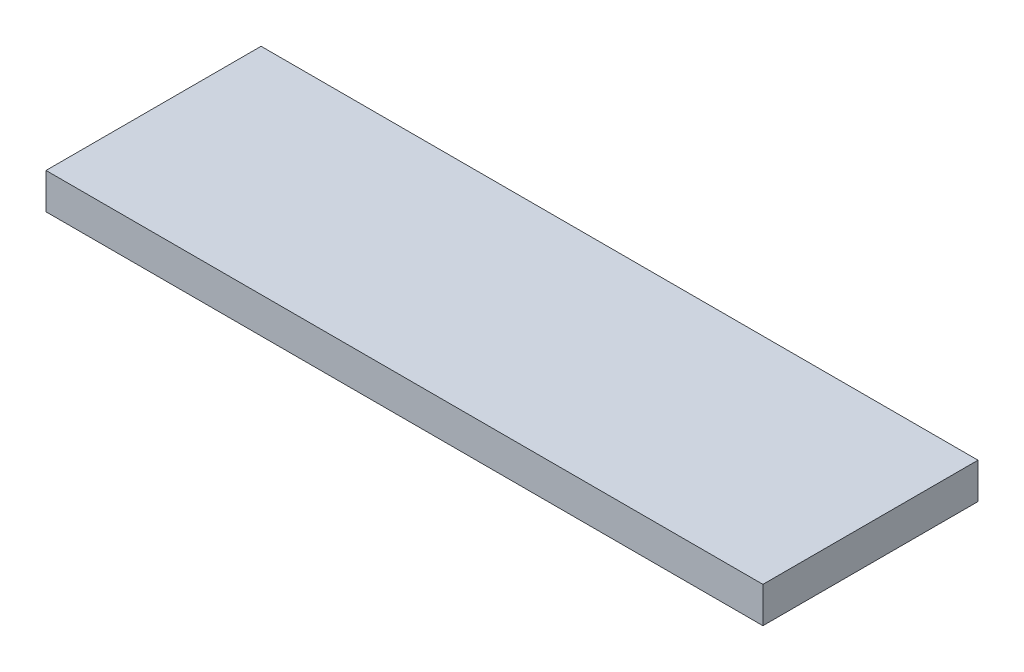
SolidWorks part; units mm, degrees
material "Custom Plastic"
ref_plane "Front Plane" through (0, 0, 0) normal (0, 0, 1) x (1, 0, 0)
ref_plane "Top Plane" through (0, 0, 0) normal (0, 1, 0) x (1, 0, 0)
ref_plane "Right Plane" through (0, 0, 0) normal (1, 0, 0) x (0, 0, -1)
sketch "Sketch1" plane through (0, 0, 0) normal (0, 1, 0) x (1, 0, 0)
  line L1 (63.5, -19.05) -> (-63.5, -19.05)
  line L2 (63.5, -19.05) -> (63.5, 19.05)
  line L3 (63.5, 19.05) -> (-63.5, 19.05)
  line L4 (-63.5, -19.05) -> (-63.5, 19.05)
  line L5 (63.5, -19.05) -> (-63.5, 19.05) construction
  line L6 (63.5, 19.05) -> (-63.5, -19.05) construction
  point P0 (0, 0)
  dimension "D1" = 127
  dimension "D2" = 38.1
extrude "Main" add sketch "Sketch1" along normal blind 6.35
sketch "Sketch2" plane through (0, 6.35, 0) normal (0, 1, 0) x (1, 0, 0)
  line L0 (-54.4505, 19.05) -> (-54.4505, 12.7)
  line L1 (63.5, 19.05) -> (-63.5, 19.05) construction
  line L2 (-54.4505, 12.7) -> (-42.2792, 12.7)
  line L3 (-42.2792, 12.7) -> (-42.2792, 19.05)
  line L4 (-42.2792, 19.05) -> (-30.1079, 19.05) construction
  line L5 (-30.1079, 19.05) -> (-30.1079, 12.7)
  line L6 (-30.1079, 12.7) -> (-17.9366, 12.7)
  line L7 (-17.9366, 12.7) -> (-17.9366, 19.05)
  line L8 (-17.9366, 19.05) -> (-5.7653, 19.05) construction
  line L9 (-5.7653, 19.05) -> (-5.7653, 12.7)
  line L10 (-5.7653, 12.7) -> (6.4059, 12.7)
  line L11 (6.4059, 12.7) -> (6.4059, 19.05)
  line L12 (6.4059, 19.05) -> (18.5772, 19.05) construction
  line L13 (18.5772, 19.05) -> (18.5772, 12.7)
  line L14 (18.5772, 12.7) -> (30.7485, 12.7)
  line L15 (30.7485, 12.7) -> (30.7485, 19.05)
  line L16 (-54.4505, 19.05) -> (-42.2792, 19.05)
  line L17 (-30.1079, 19.05) -> (-17.9366, 19.05)
  line L18 (-17.9366, 19.05) -> (-17.9366, 19.2979)
  line L19 (-5.7653, 19.05) -> (6.4059, 19.05)
  line L20 (6.4059, 19.05) -> (7.0465, 19.4581)
  line L21 (18.5772, 19.05) -> (30.7485, 19.05)
  dimension "D1" = 6.35
